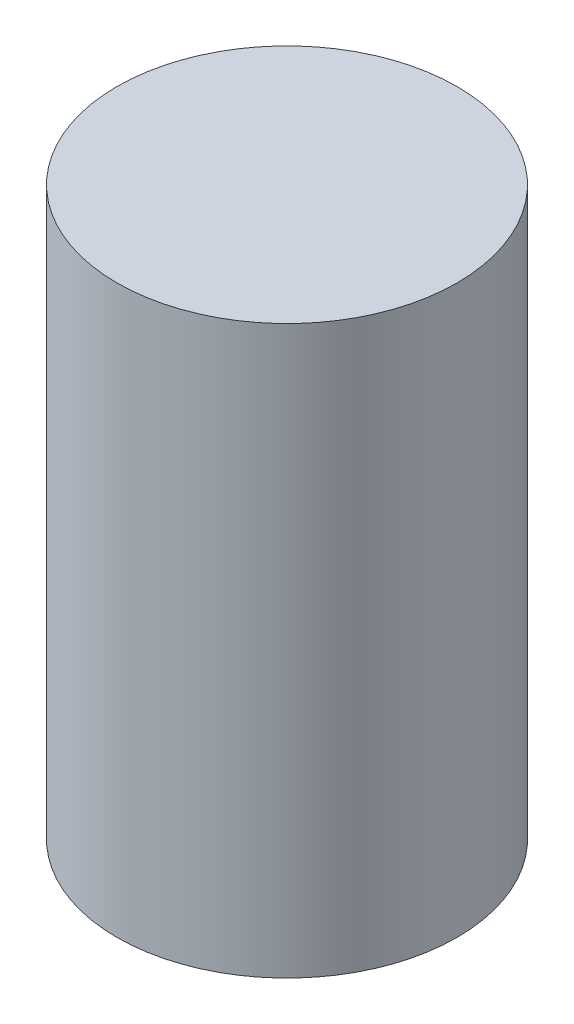
SolidWorks part; units mm, degrees
ref_plane "Front Plane" through (0, 0, 0) normal (0, 0, 1) x (1, 0, 0)
ref_plane "Top Plane" through (0, 0, 0) normal (0, 1, 0) x (1, 0, 0)
ref_plane "Right Plane" through (0, 0, 0) normal (1, 0, 0) x (0, 0, -1)
sketch "Sketch1" plane through (0, 0, 0) normal (0, 1, 0) x (1, 0, 0)
  circle A0 centre (0, 0) radius 30
  dimension "D1" = 60
extrude "Boss-Extrude1" add sketch "Sketch1" along normal blind 100
